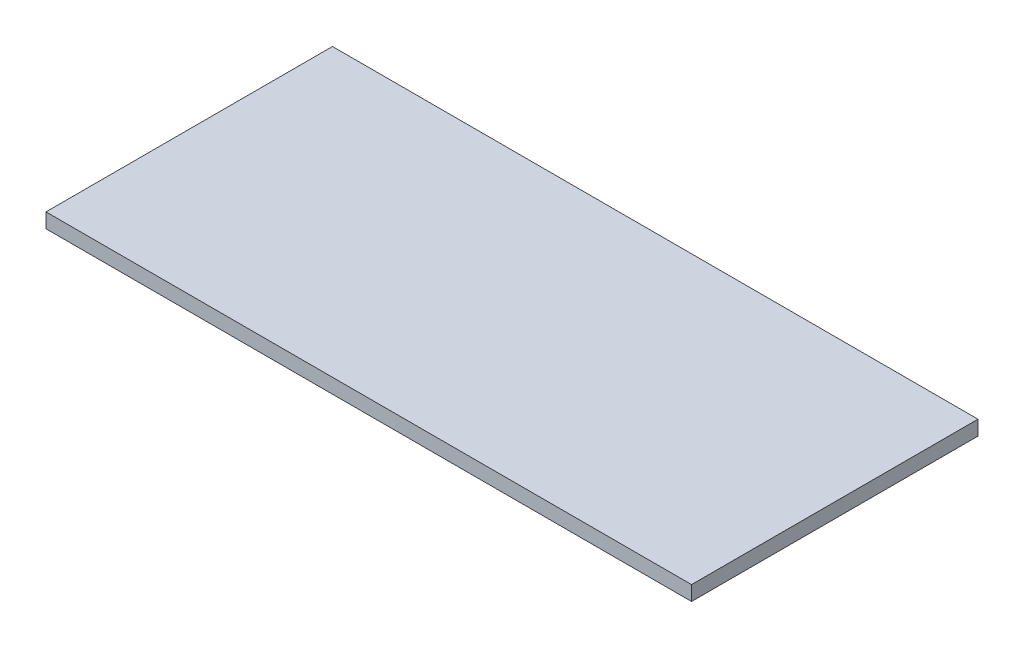
SolidWorks part; units mm, degrees
ref_plane "Alzado" through (0, 0, 0) normal (0, 0, 1) x (1, 0, 0)
ref_plane "Planta" through (0, 0, 0) normal (0, 1, 0) x (1, 0, 0)
ref_plane "Vista lateral" through (0, 0, 0) normal (1, 0, 0) x (0, 0, -1)
sketch "Croquis1" plane through (0, 0, 0) normal (0, 1, 0) x (1, 0, 0)
  line L1 (-44, 19.525) -> (44, 19.525)
  line L2 (-44, 19.525) -> (-44, -19.525)
  line L3 (-44, -19.525) -> (44, -19.525)
  line L4 (44, 19.525) -> (44, -19.525)
  line L5 (-44, 19.525) -> (44, -19.525) construction
  line L6 (-44, -19.525) -> (44, 19.525) construction
  point P0 (0, 0)
  dimension "D1" = 88
  dimension "D2" = 39.05
extrude "Saliente-Extruir1" add sketch "Croquis1" along normal blind 2
